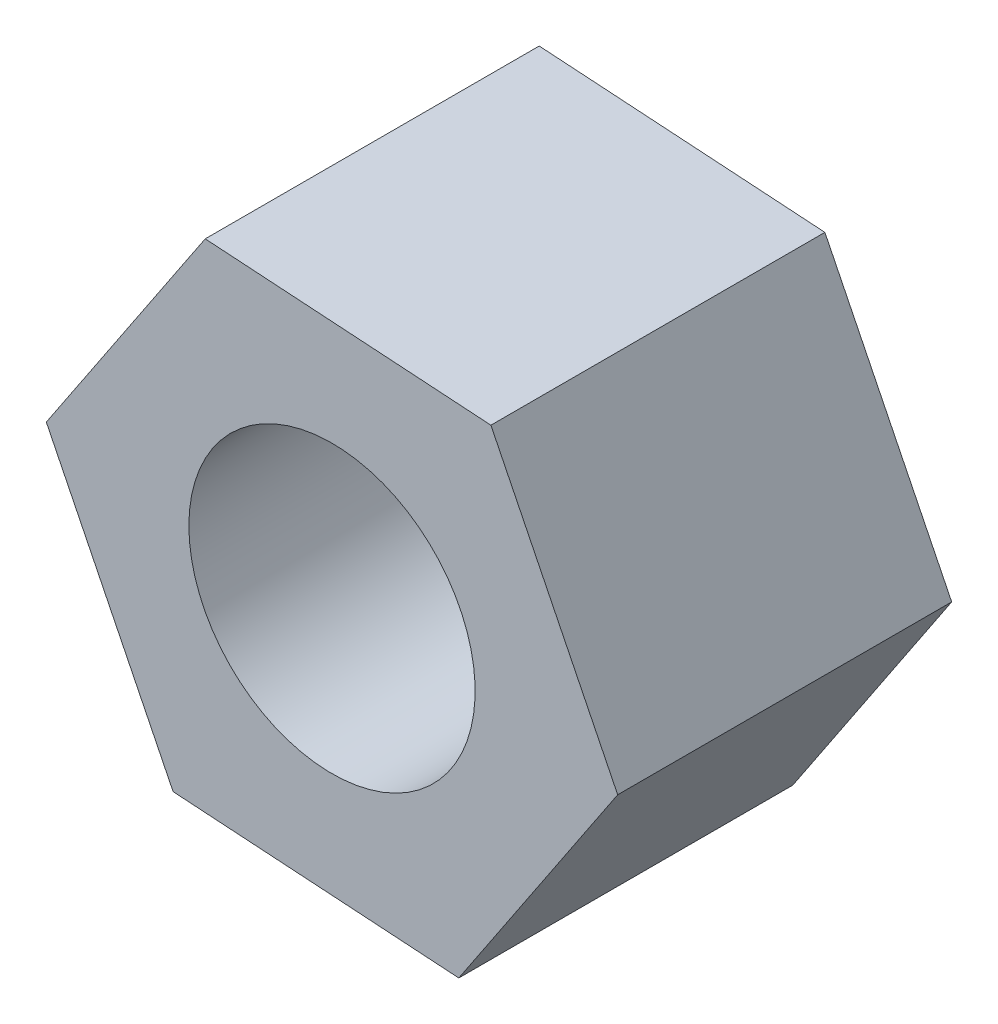
SolidWorks part; units mm, degrees
ref_plane "Front Plane" through (0, 0, 0) normal (0, 0, 1) x (1, 0, 0)
ref_plane "Top Plane" through (0, 0, 0) normal (0, 1, 0) x (1, 0, 0)
ref_plane "Right Plane" through (0, 0, 0) normal (1, 0, 0) x (0, 0, -1)
sketch "Sketch1" plane through (0, 0, 0) normal (0, 0, 1) x (1, 0, 0)
  line L1 (-59.874, 3.8865) -> (-33.3028, -49.9091)
  line L2 (-33.3028, -49.9091) -> (26.5712, -53.7957)
  line L3 (26.5712, -53.7957) -> (59.874, -3.8865)
  line L4 (59.874, -3.8865) -> (33.3028, 49.9091)
  line L5 (33.3028, 49.9091) -> (-26.5712, 53.7957)
  line L6 (-26.5712, 53.7957) -> (-59.874, 3.8865)
  circle A0 centre (0, 0) radius 51.9615 construction
  circle A1 centre (0, 0) radius 30
  dimension "D1" = 60
  dimension "D2" = 120
extrude "Boss-Extrude1" add sketch "Sketch1" along normal blind 70
cosmetic thread "Cosmetic Thread1" parameters "D2"=64
